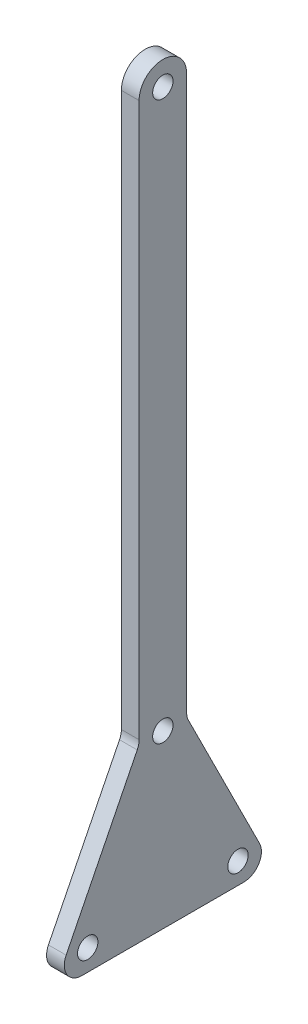
SolidWorks part; units mm, degrees
ref_plane "Front Plane" through (0, 0, 0) normal (0, 0, 1) x (1, 0, 0)
ref_plane "Top Plane" through (0, 0, 0) normal (0, 1, 0) x (1, 0, 0)
ref_plane "Right Plane" through (0, 0, 0) normal (1, 0, 0) x (0, 0, -1)
sketch "Sketch1" plane through (0, 0, 0) normal (1, 0, 0) x (0, 0, -1)
  line L0 (-13.4747, 0) -> (13.4747, 0) construction
  line L1 (0, 0) -> (0, 26.9494) construction
  line L2 (-13.4747, 0) -> (0, 26.9494) construction
  line L3 (0, 26.9494) -> (13.4747, 0) construction
  line L4 (13.4747, 0) -> (-13.4747, 0) construction
  line L5 (19.6394, -3.81) -> (-19.6394, -3.81)
  line L6 (-19.6394, -3.81) -> (0, 35.4688)
  line L7 (0, 35.4688) -> (19.6394, -3.81)
  line L8 (0, 26.9494) -> (0, 126.9494) construction
  line L9 (0, 126.9494) -> (0, 26.9494) construction
  line L10 (4.2597, 126.9494) -> (4.2597, 26.9494)
  line L11 (-4.2597, 126.9494) -> (-4.2597, 26.9494)
  circle A0 centre (-13.4747, 0) radius 1.8288
  circle A1 centre (0, 26.9494) radius 1.8288
  circle A2 centre (13.4747, 0) radius 1.8288
  circle A3 centre (0, 126.9494) radius 1.8288
  arc A4 (4.2597, 126.9494) -> (-4.2597, 126.9494) centre (0, 126.9494) ccw
  arc A5 (-4.2597, 26.9494) -> (4.2597, 26.9494) centre (0, 26.9494) ccw
  point P4 (0, 0)
  point P14 (0, 76.9494)
  dimension "D3" = 3.6576
  dimension "D1" = 26.9494
  dimension "D5" = 100
  dimension "D2" = 3.81
extrude "Boss-Extrude1" add sketch "Sketch1" along normal blind 3.175 contours A5 L6 L5 L7 A2 A0 | L6 A5 L7 A1 | L10 A4 L11 L6 L7 A3
fillet "Fillet1" radius 3.175 4 edges at (1.5875, -3.81, -19.6394) (1.5875, -3.81, 19.6394) (1.5875, 26.9494, 4.2597) (1.5875, 26.9494, -4.2597)
